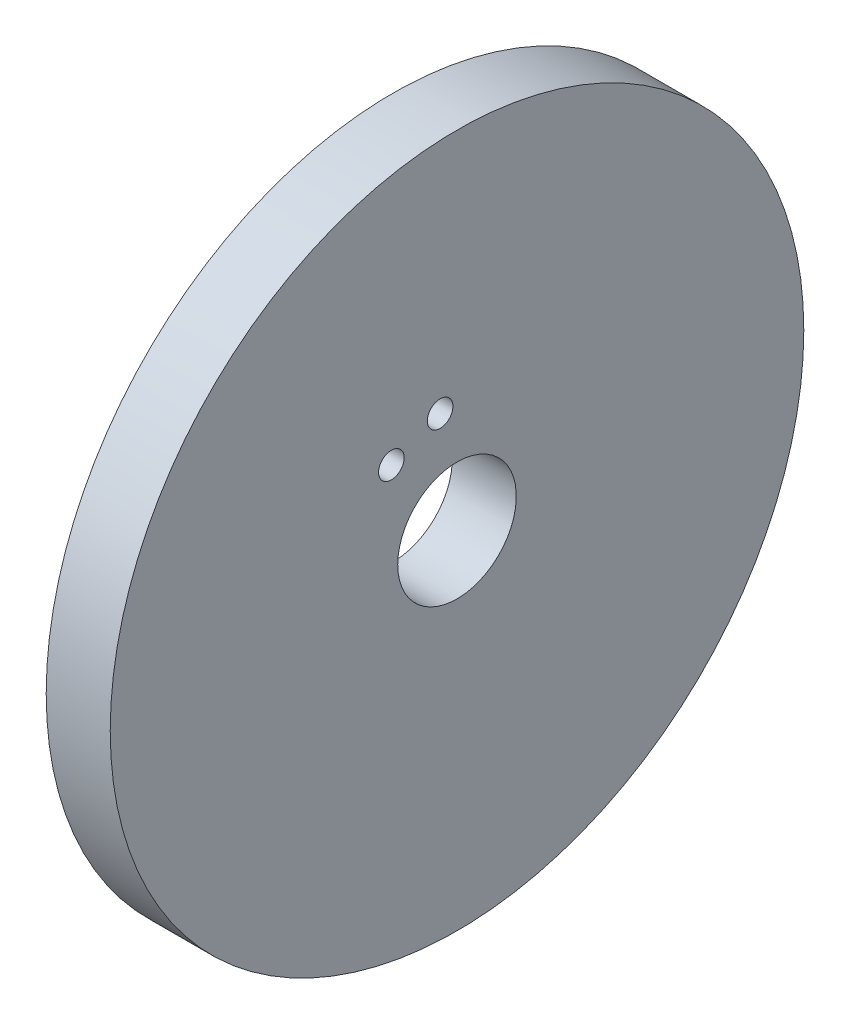
SolidWorks part; units mm, degrees
material "AISI 304"
ref_plane "Front Plane" through (0, 0, 0) normal (0, 0, 1) x (1, 0, 0)
ref_plane "Top Plane" through (0, 0, 0) normal (0, 1, 0) x (1, 0, 0)
ref_plane "Right Plane" through (0, 0, 0) normal (1, 0, 0) x (0, 0, -1)
sketch "Axial profile (mm)" plane through (0, 0, 0) normal (0, 0, 1) x (1, 0, 0)
  line L0 (-110, 0) -> (75, 0) construction
  line L1 (13.7, 11.1125) -> (25.7, 11.1125)
  line L2 (25.7, 11.1125) -> (25.7, 65)
  line L3 (25.7, 65) -> (13.7, 65)
  line L4 (13.7, 65) -> (13.7, 11.1125)
revolve "Full revolution" add sketch "Axial profile (mm)" angle 360 about L0
sketch "Sketch2" plane through (0, 0, 0) normal (1, 0, 0) x (0, 0, -1)
  circle A0 centre (-3.1638, 20.558) radius 2.4
  circle A1 centre (-12.2995, 16.7738) radius 2.4
extrude "Axial holes" cut sketch "Sketch2" along normal through all and the other way through all
